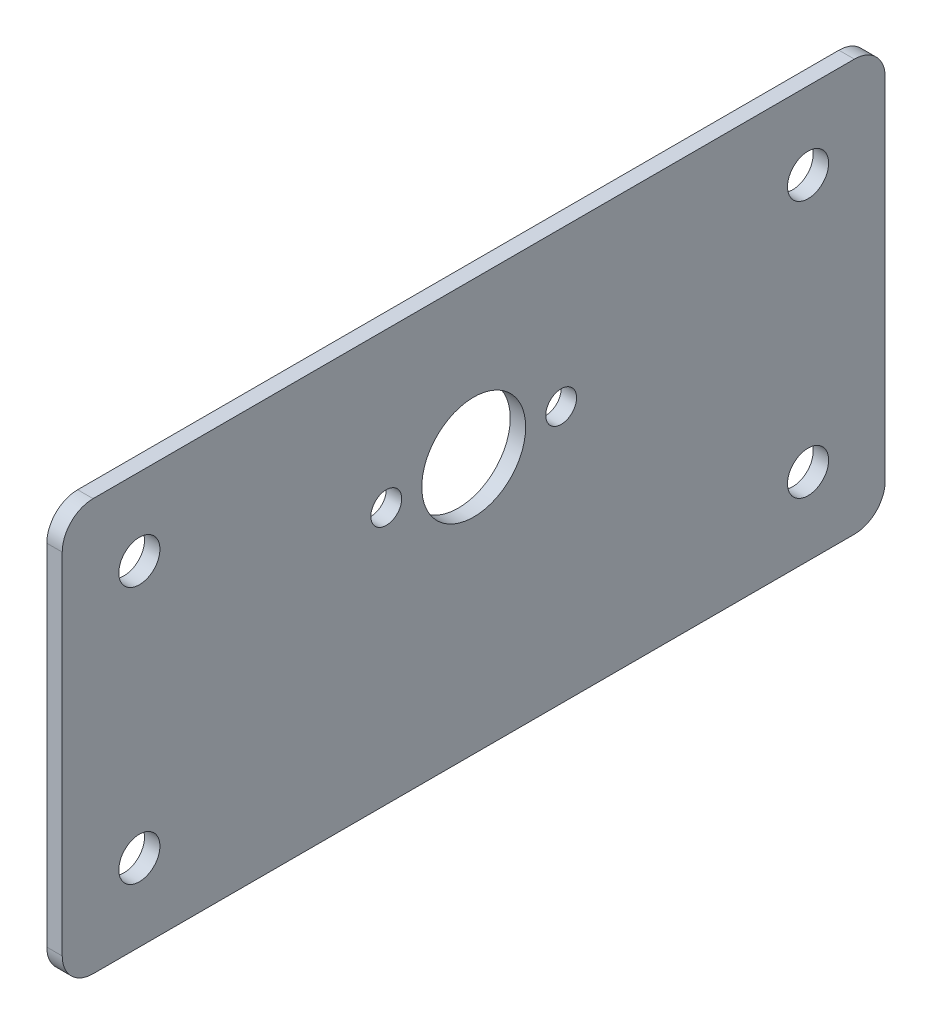
SolidWorks part; units mm, degrees
material "1060 合金"
ref_plane "正面" through (0, 0, 0) normal (0, 0, 1) x (1, 0, 0)
ref_plane "平面" through (0, 0, 0) normal (0, 1, 0) x (1, 0, 0)
ref_plane "右側面" through (0, 0, 0) normal (1, 0, 0) x (0, 0, -1)
sketch "ｽｹｯﾁ1" plane through (0, 0, 0) normal (1, 0, 0) x (0, 0, -1)
  line L0 (0, -3.416) -> (0, 5295.0834) construction
  line L1 (-40, -20) -> (40, -20)
  line L2 (-40, -20) -> (-40, 20)
  line L3 (-40, 20) -> (40, 20)
  line L4 (40, -20) -> (40, 20)
  line L5 (-40, -20) -> (40, 20) construction
  line L6 (-40, 20) -> (40, -20) construction
  line L7 (0, 0) -> (5298.4994, 0) construction
  line L8 (0, 5) -> (8.5, 5) construction
  line L11 (32.5, 20) -> (32.5, -20) construction
  circle A13 centre (32.5, 12.5) radius 2
  circle A16 centre (-32.5, 12.5) radius 2
  circle A17 centre (32.5, -12.5) radius 2
  circle A18 centre (0, 5) radius 5.05
  circle A19 centre (-32.5, -12.5) radius 2
  circle A20 centre (8.5, 5) radius 1.5
  circle A21 centre (-8.5, 5) radius 1.5
  point P0 (0, 0)
  dimension "D2" = 25
  dimension "D3" = 7.5
  dimension "D4" = 7.5
  dimension "D6" = 10.1
  dimension "D7" = 17
  dimension "D8" = 3
  dimension "D5" = 15
  dimension "D10" = 7.5
  dimension "D11" = 4
  dimension "D12" = 80
extrude "ﾎﾞｽ - 押し出し1" add sketch "ｽｹｯﾁ1" along normal blind 1.5
fillet "ﾌｨﾚｯﾄ1" radius 3 4 edges at (0.75, -20, 40) (0.75, -20, -40) (0.75, 20, -40) (0.75, 20, 40)
